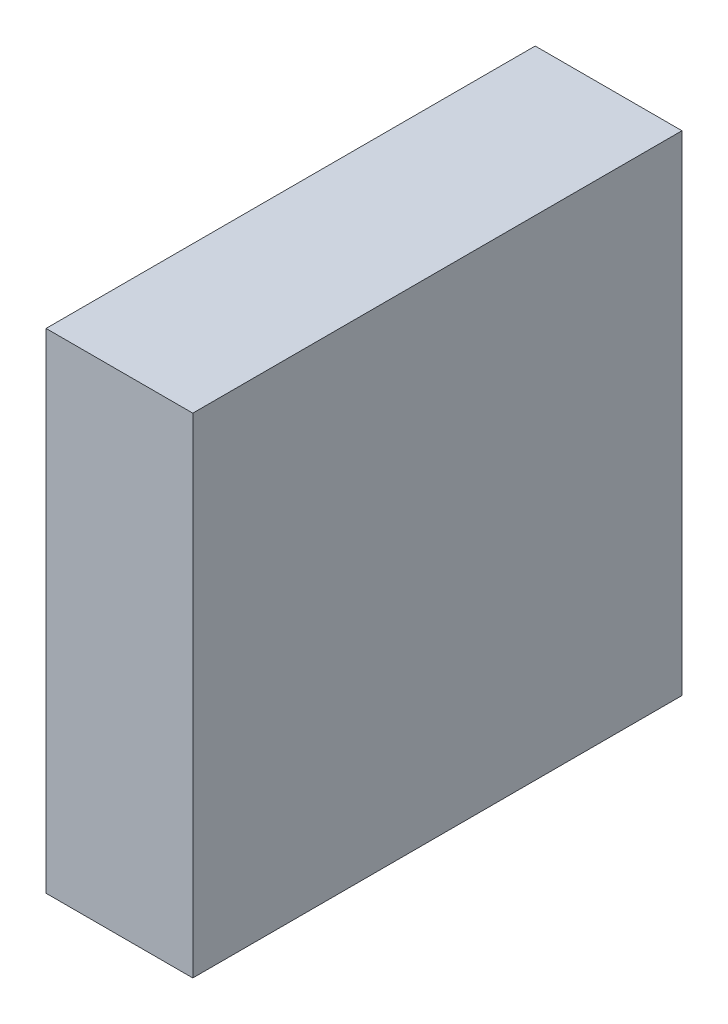
SolidWorks part; units mm, degrees
ref_plane "Front Plane" through (0, 0, 0) normal (0, 0, 1) x (1, 0, 0)
ref_plane "Top Plane" through (0, 0, 0) normal (0, 1, 0) x (1, 0, 0)
ref_plane "Right Plane" through (0, 0, 0) normal (1, 0, 0) x (0, 0, -1)
sketch "Sketch1" plane through (0, 0, 0) normal (1, 0, 0) x (0, 0, -1)
  line L1 (-1.5, 1.5) -> (1.5, 1.5)
  line L2 (-1.5, 1.5) -> (-1.5, -1.5)
  line L3 (-1.5, -1.5) -> (1.5, -1.5)
  line L4 (1.5, 1.5) -> (1.5, -1.5)
  line L5 (-1.5, 1.5) -> (1.5, -1.5) construction
  line L6 (-1.5, -1.5) -> (1.5, 1.5) construction
  point P0 (0, 0)
  dimension "D1" = 3
  dimension "D2" = 3
extrude "Boss-Extrude1" add sketch "Sketch1" along normal blind 0.9
